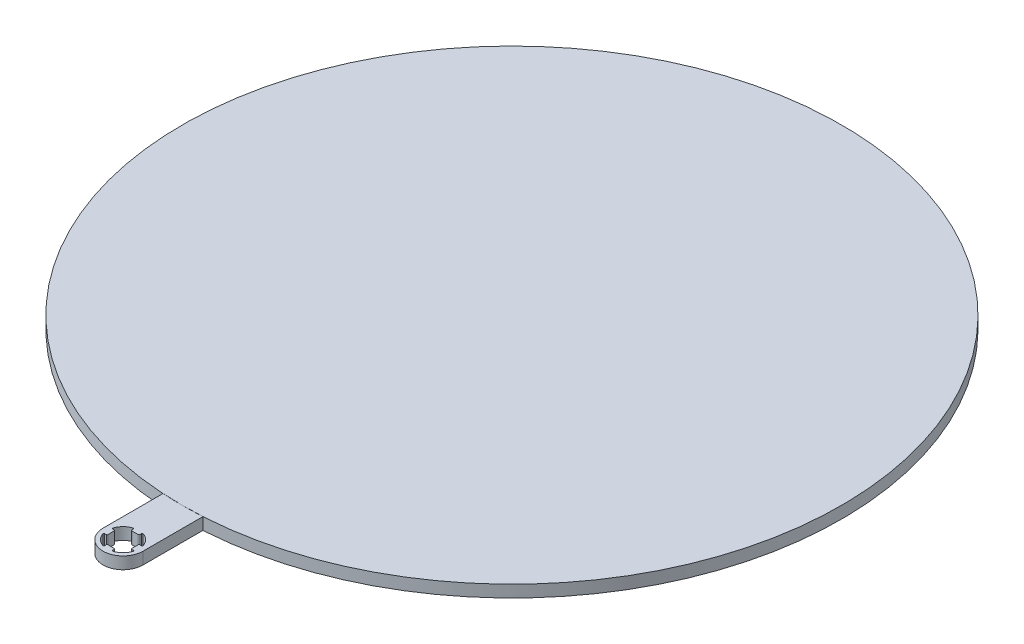
SolidWorks part; units mm, degrees
ref_plane "Front Plane" through (0, 0, 0) normal (0, 0, 1) x (1, 0, 0)
ref_plane "Top Plane" through (0, 0, 0) normal (0, 1, 0) x (1, 0, 0)
ref_plane "Right Plane" through (0, 0, 0) normal (1, 0, 0) x (0, 0, -1)
sketch "Sketch1" plane through (0, 0, 0) normal (0, 1, 0) x (1, 0, 0)
  circle A0 centre (0, 0) radius 82.5
  dimension "D1" = 165
extrude "Boss-Extrude1" add sketch "Sketch1" along normal blind 3
sketch "Sketch11" plane through (0, 3, 0) normal (0, 1, 0) x (1, 0, 0)
  line L1 (-5, -82.3483) -> (5, -82.3483)
  line L2 (-5, -82.3483) -> (-5, -97.3483)
  line L4 (5, -82.3483) -> (5, -97.3483)
  circle A0 centre (0, 0) radius 82.5 construction
  arc A1 (-5, -97.3483) -> (5, -97.3483) centre (0, -97.3483) ccw
  circle A2 centre (0, -97.3483) radius 4
  circle M10 centre (0, 0) radius 82.5
  dimension "D3" = 8
  dimension "D1" = 10
  dimension "D2" = 15
extrude "Boss-Extrude8" add sketch "Sketch11" against normal through all separate body contours L2 A1 L4 A2 M10
sketch "Sketch12" plane through (0, 3, 0) normal (0, 1, 0) x (1, 0, 0)
  line L0 (-1, -93.4754) -> (-1, -94.3483)
  line L1 (-1, -94.3483) -> (1, -94.3483)
  line L2 (1, -94.3483) -> (1, -93.4754)
  line L3 (3.873, -96.3483) -> (3, -96.3483)
  line L4 (3, -96.3483) -> (3, -98.3483)
  line L5 (3, -98.3483) -> (3.873, -98.3483)
  line L6 (1, -101.2213) -> (1, -100.3483)
  line L7 (1, -100.3483) -> (-1, -100.3483)
  line L8 (-1, -100.3483) -> (-1, -101.2213)
  line L9 (-3.873, -98.3483) -> (-3, -98.3483)
  line L10 (-3, -98.3483) -> (-3, -96.3483)
  line L11 (-3, -96.3483) -> (-3.873, -96.3483)
  circle A0 centre (0, -97.3483) radius 4 construction
  arc A1 (1, -93.4754) -> (-1, -93.4754) centre (0, -97.3483) ccw
  arc A2 (3.873, -98.3483) -> (3.873, -96.3483) centre (0, -97.3483) ccw
  arc A3 (-1, -101.2213) -> (1, -101.2213) centre (0, -97.3483) ccw
  arc A4 (-3.873, -96.3483) -> (-3.873, -98.3483) centre (0, -97.3483) ccw
  point P22 (0, -97.3483)
  dimension "D1" = 1
  dimension "D2" = 2
  dimension "D3" = 4
extrude "Boss-Extrude9" add sketch "Sketch12" against normal through all
fillet "Fillet1" radius 0.2 16 edges at (1, 1.5, 93.4754) (-1, 1.5, 93.4754) (1, 1.5, 94.3483) (-1, 1.5, 94.3483) (1, 1.5, 101.2213) (1, 1.5, 100.3483) (-1, 1.5, 100.3483) (-1, 1.5, 101.2213) (3.873, 1.5, 98.3483) (3, 1.5, 98.3483) (3.873, 1.5, 96.3483) (3, 1.5, 96.3483) (-3.873, 1.5, 96.3483) (-3.873, 1.5, 98.3483) (-3, 1.5, 96.3483) (-3, 1.5, 98.3483)
